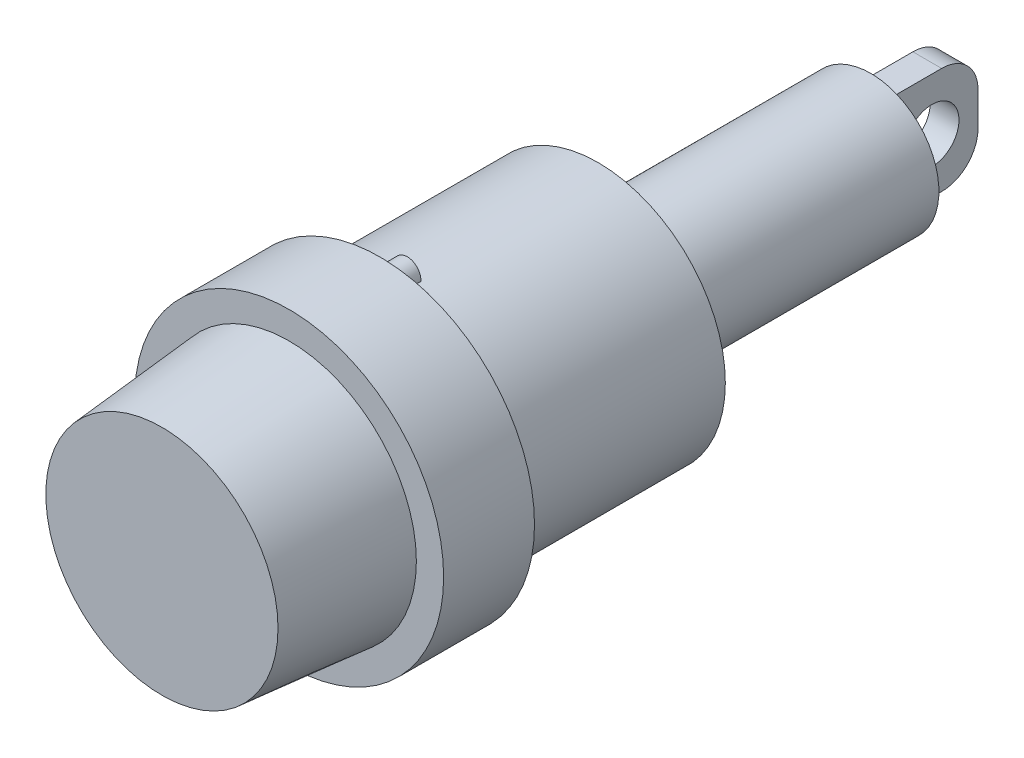
SolidWorks part; units mm, degrees
ref_plane "Спереди" through (0, 0, 0) normal (0, 0, 1) x (1, 0, 0)
ref_plane "Сверху" through (0, 0, 0) normal (0, 1, 0) x (1, 0, 0)
ref_plane "Справа" through (0, 0, 0) normal (1, 0, 0) x (0, 0, -1)
sketch "Эскиз1" plane through (0, 0, 0) normal (0, 0, 1) x (1, 0, 0)
  circle A0 centre (0, 0) radius 8.5
  dimension "D1" = 17
extrude "Бобышка-Вытянуть1" add sketch "Эскиз1" along normal blind 5
sketch "Эскиз2" plane through (0, 0, 5) normal (0, 0, 1) x (1, 0, 0)
  circle A0 centre (0, 0) radius 7
  dimension "D1" = 14
extrude "Бобышка-Вытянуть2" add sketch "Эскиз2" along normal blind 7 draft 5
sketch "Эскиз3" plane through (0, 0, 0) normal (0, 0, -1) x (-1, 0, 0)
  circle A0 centre (0, 0) radius 7
  dimension "D1" = 14
extrude "Бобышка-Вытянуть3" add sketch "Эскиз3" along normal blind 12
sketch "Эскиз4" plane through (0, 0, -12) normal (0, 0, -1) x (-1, 0, 0)
  circle A0 centre (0, 0) radius 3.75
  dimension "D1" = 7.5
extrude "Бобышка-Вытянуть4" add sketch "Эскиз4" along normal blind 15
sketch "Эскиз5" plane through (0, 0, -27) normal (0, 0, -1) x (-1, 0, 0)
  line L1 (-0.9013, 2.9347) -> (0.6815, 2.9347)
  line L2 (-0.9013, 2.9347) -> (-0.9013, -2.9347)
  line L3 (-0.9013, -2.9347) -> (0.6815, -2.9347)
  line L4 (0.6815, 2.9347) -> (0.6815, -2.9347)
extrude "Бобышка-Вытянуть5" add sketch "Эскиз5" along normal blind 5
sketch "Эскиз6" plane through (0.9013, 0, 0) normal (1, 0, 0) x (0, 0, -1)
  circle A0 centre (29.4675, 0) radius 1.4841
extrude "Вырез-Вытянуть1" cut sketch "Эскиз6" against normal blind 5
fillet "Скругление1" radius 2 2 edges at (0.1099, -2.9347, -32) (0.1099, 2.9347, -32)
sketch "Эскиз7" plane through (0, 0, 0) normal (0, 0, -1) x (-1, 0, 0)
  line L0 (0, 8.5) -> (0, -8.5) construction
  circle A0 centre (0, 0) radius 8.5 construction
  circle A1 centre (0, 7.0107) radius 0.75
  dimension "D1" = 1.5
extrude "Бобышка-Вытянуть6" add sketch "Эскиз7" along normal blind 1.5
